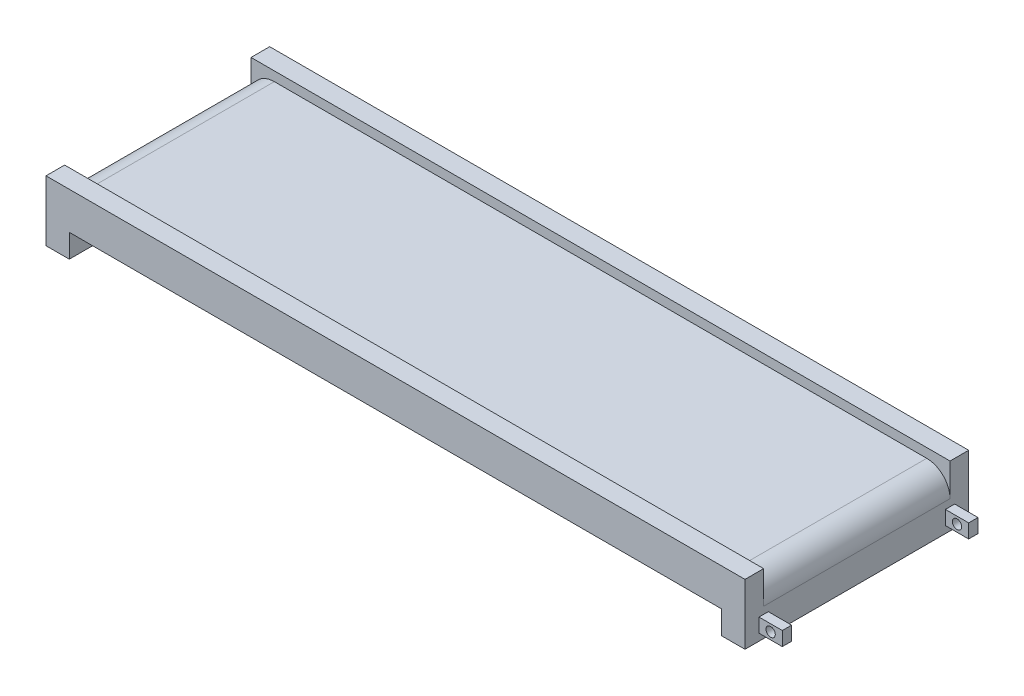
SolidWorks part; units mm, degrees
ref_plane "Front Plane" through (0, 0, 0) normal (0, 0, 1) x (1, 0, 0)
ref_plane "Top Plane" through (0, 0, 0) normal (0, 1, 0) x (1, 0, 0)
ref_plane "Right Plane" through (0, 0, 0) normal (1, 0, 0) x (0, 0, -1)
sketch "Sketch3" plane through (0, 0, 0) normal (0, 1, 0) x (1, 0, 0)
  line L0 (0, 0) -> (3810, 0)
  line L1 (3810, 0) -> (3810, -1219.2)
  line L2 (3810, -1219.2) -> (0, -1219.2)
  line L3 (0, -1219.2) -> (0, 0)
extrude "Boss-Extrude2" add sketch "Sketch3" along normal blind 203.2
sketch "Sketch4" plane through (0, 203.2, 0) normal (0, 1, 0) x (1, 0, 0)
  line L0 (0, 0) -> (0, -101.6)
  line L1 (0, 0) -> (0, -1219.2) construction
  line L2 (0, -101.6) -> (3810, -101.6)
  line L3 (3810, -1219.2) -> (3810, 0) construction
  line L4 (3810, -101.6) -> (3810, -1117.6)
  line L5 (3810, -1117.6) -> (0, -1117.6)
  line L6 (0, -1117.6) -> (0, -101.6)
  line M1 (0, 0) -> (0, -1219.2)
  line M3 (3810, -1219.2) -> (3810, 0)
extrude "Cut-Extrude1" cut sketch "Sketch4" against normal blind 50.8 contours L5 L2 M3 M1
sketch "Sketch5" plane through (0, 0, 0) normal (0, -1, 0) x (-1, 0, 0)
  line L0 (0, -1219.2) -> (-127, -1219.2)
  line L1 (0, -1219.2) -> (-3810, -1219.2) construction
  line L2 (-127, -1219.2) -> (-127, 0)
  line L3 (-3810, 0) -> (0, 0) construction
  line L4 (-127, 0) -> (0, 0)
  line L5 (0, 0) -> (0, -1219.2)
  line L6 (-3810, -1219.2) -> (-3683, -1219.2)
  line L7 (-3683, -1219.2) -> (-3683, 0)
  line L8 (-3810, -1219.2) -> (-3810, 0)
  line M1 (0, -1219.2) -> (0, 0)
  line M2 (0, 0) -> (-3810, 0)
  line M3 (-3810, 0) -> (-3810, -1219.2)
  line M4 (-3810, -1219.2) -> (0, -1219.2)
extrude "Boss-Extrude3" add sketch "Sketch5" along normal blind 127 contours L2 M4 M1 M2 | L7 M4 M2 M3
fillet "Fillet2" radius 127 2 edges at (0, 152.4, 609.6) (3810, 152.4, 609.6)
sketch "Sketch6" plane through (3810, 0, 0) normal (1, 0, 0) x (0, 0, -1)
  line L0 (-1117.6, 25.4) -> (-1117.6, -50.8)
  line L1 (-1117.6, -50.8) -> (-101.6, -50.8)
  line L2 (-101.6, -50.8) -> (-101.6, 25.4)
  line L3 (-101.6, 25.4) -> (-1117.6, 25.4) construction
  line L4 (-101.6, 25.4) -> (-101.6, -12.7)
  line L5 (-101.6, -12.7) -> (-76.2, -12.7)
  line L6 (-76.2, -12.7) -> (-76.2, -88.9)
  line L7 (-76.2, -88.9) -> (-127, -88.9)
  line L8 (-127, -88.9) -> (-127, -12.7)
  line L9 (-127, -12.7) -> (-101.6, -12.7)
  line L10 (-1117.6, -12.7) -> (-1092.2, -12.7)
  line L11 (-1092.2, -12.7) -> (-1092.2, -88.9)
  line L12 (-1092.2, -88.9) -> (-1143, -88.9)
  line L13 (-1143, -88.9) -> (-1143, -12.7)
  line L14 (-1143, -12.7) -> (-1117.6, -12.7)
extrude "Boss-Extrude4" add sketch "Sketch6" along normal blind 127 contours L11 L10 L0 L1 | L14 L13 L12 L11 L1 L0 | L8 L7 L6 L5 L2 L1 | L9 L8 L1 L2
sketch "Sketch7" plane through (0, 0, 1143) normal (0, 0, 1) x (1, 0, 0)
  line L0 (3810, -50.8) -> (3873.5, -50.8)
  line L1 (3810, -88.9) -> (3810, -12.7) construction
  circle A0 centre (3873.5, -50.8) radius 25.4
extrude "Cut-Extrude2" cut sketch "Sketch7" against normal blind 1270
